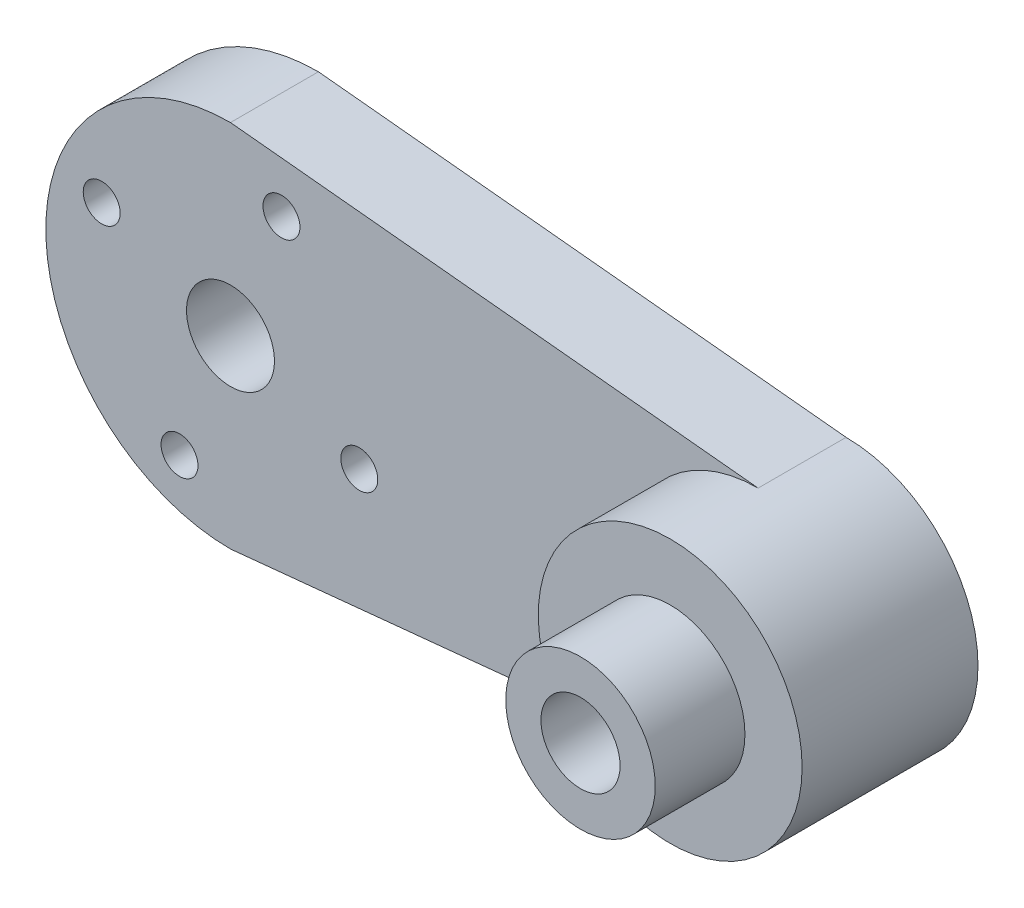
SolidWorks part; units mm, degrees
ref_plane "Front" through (0, 0, 0) normal (0, 0, 1) x (1, 0, 0)
ref_plane "Top" through (0, 0, 0) normal (0, 1, 0) x (1, 0, 0)
ref_plane "Right" through (0, 0, 0) normal (1, 0, 0) x (0, 0, -1)
sketch "스케치1" plane through (0, 0, 0) normal (0, 0, 1) x (1, 0, 0)
  line L0 (0, 0) -> (30, 0) construction
  line L1 (0, 10.5) -> (30, 7.5)
  line L2 (30, -7.5) -> (0, -10.5)
  line L3 (30, 7.5) -> (30, -7.5) construction
  line L4 (0, 10.5) -> (0, -10.5) construction
  arc A0 (0, 10.5) -> (0, -10.5) centre (0, 0) ccw
  circle A1 centre (0, 0) radius 2.5
  arc A2 (30, -7.5) -> (30, 7.5) centre (30, 0) ccw
  dimension "D1" = 5
  dimension "D2" = 21
  dimension "D3" = 15
  dimension "D4" = 30
extrude "보스-돌출1" add sketch "스케치1" along normal blind 5
sketch "스케치2" plane through (0, 0, 5) normal (0, 0, 1) x (1, 0, 0)
  circle A0 centre (30, 0) radius 7.5
  arc A1 (30, -7.5) -> (30, 7.5) centre (30, 0) ccw construction
  dimension "D1" = 15
extrude "보스-돌출2" add sketch "스케치2" along normal blind 5
sketch "스케치3" plane through (0, 0, 10) normal (0, 0, 1) x (1, 0, 0)
  circle A0 centre (30, 0) radius 4.25
  circle A1 centre (30, 0) radius 7.5 construction
  dimension "D1" = 8.5
extrude "보스-돌출3" add sketch "스케치3" along normal blind 5.1
sketch "스케치4" plane through (0, 0, 15.1) normal (0, 0, 1) x (1, 0, 0)
  circle A0 centre (30, 0) radius 2.25
  circle A1 centre (30, 0) radius 4.25 construction
  dimension "D1" = 4.5
extrude "컷-돌출1" cut sketch "스케치4" against normal blind 36.1
hole_wizard "M1.8 여유 구멍1" positions "스케치5" profile "스케치6" hole size "M1.8" standard "KS" end condition up to next
sketch "스케치5" plane through (0, 0, 0) normal (0, 0, -1) x (-1, 0, 0)
  point P0 (2.8975, -7.3226)
  point P6 (-7.3226, -2.8975)
  point P12 (7.3226, 2.8975)
  point P21 (-2.8975, 7.3226)
sketch "스케치6" plane through (-2.8975, -7.3226, 0) normal (1, 0, 0) x (0, 1, 0)
  line L0 (0, 0) -> (0, 5)
  line L1 (0, 5) -> (1.05, 5)
  line L2 (1.05, 5) -> (1.05, 0)
  line L5 (1.05, 0) -> (0, 0)
  line L11 (0, -6.35) -> (0, 107.95) construction
  dimension "관통 구멍 지름" = 2.1
  dimension "관통 구멍 깊이" = 5
